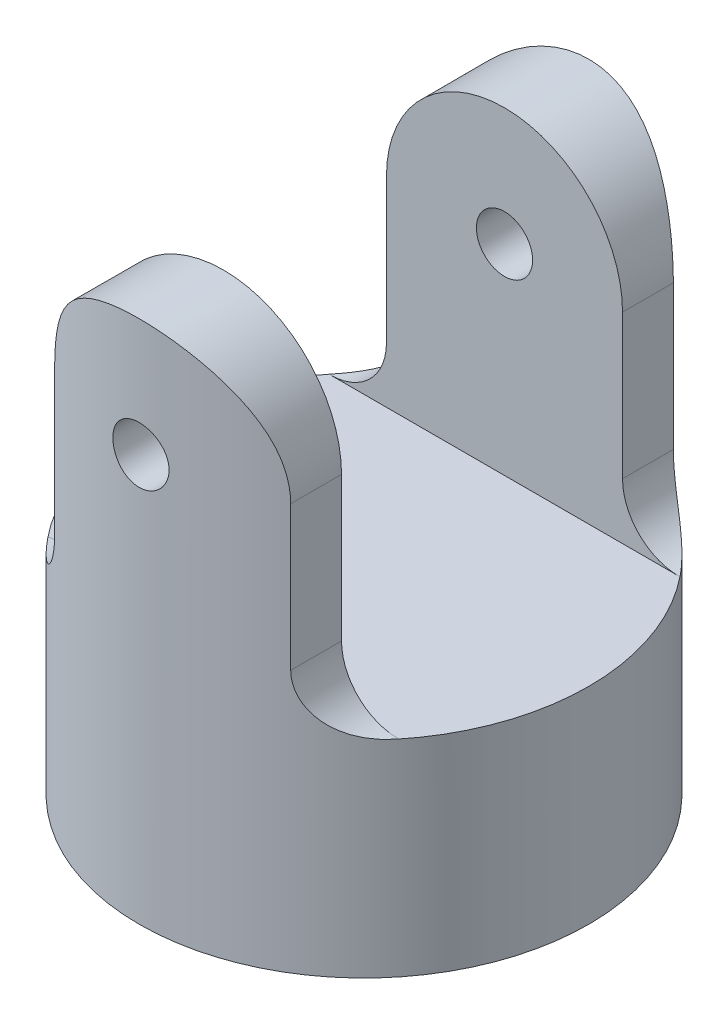
SolidWorks part; units mm, degrees
ref_plane "Front Plane" through (0, 0, 0) normal (0, 0, 1) x (1, 0, 0)
ref_plane "Top Plane" through (0, 0, 0) normal (0, 1, 0) x (1, 0, 0)
ref_plane "Right Plane" through (0, 0, 0) normal (1, 0, 0) x (0, 0, -1)
sketch "Sketch1" plane through (0, 0, 0) normal (0, 1, 0) x (1, 0, 0)
  circle A0 centre (0, 0) radius 6
  dimension "D1" = 12
extrude "Boss-Extrude1" add sketch "Sketch1" along normal blind 14
sketch "Sketch2" plane through (0, 0, 0) normal (1, 0, 0) x (0, 0, -1)
  line L0 (6, 14) -> (-6, 14) construction
  line L1 (-3.75, 14) -> (3.75, 14)
  line L2 (-3.75, 14) -> (-3.75, 5.5)
  line L3 (-3.75, 5.5) -> (3.75, 5.5)
  line L4 (3.75, 14) -> (3.75, 5.5)
  line L5 (-6, 0) -> (6, 0) construction
  point P8 (0, 5.5)
  dimension "D1" = 5.5
  dimension "D2" = 7.5
extrude "Cut-Extrude1" cut sketch "Sketch2" against normal through all both and the other way through all contours L2 L1 L4 L3
sketch "Sketch3" plane through (0, 0, 0) normal (0, 0, 1) x (1, 0, 0)
  line L0 (4.6837, 14) -> (-4.6837, 14) construction
  line L1 (-3.15, 10.85) -> (-3.15, 7)
  line L2 (-4.65, 5.5) -> (-4.6837, 5.5)
  line L3 (-4.6837, 14) -> (-4.6837, 5.5) construction
  line L4 (4.6837, 14) -> (-4.6837, 14)
  line L5 (-4.6837, 14) -> (-4.6837, 5.5)
  line L7 (0, -6.6) -> (0, 6.6) construction
  line L8 (4.6837, 14) -> (4.6837, 5.5)
  line L9 (4.65, 5.5) -> (4.6837, 5.5)
  line L10 (3.15, 10.85) -> (3.15, 7)
  arc A0 (3.15, 10.85) -> (-3.15, 10.85) centre (0, 10.85) ccw
  arc A1 (-3.15, 7) -> (-4.65, 5.5) centre (-4.65, 7) cw
  arc A2 (3.15, 7) -> (4.65, 5.5) centre (4.65, 7) ccw
  circle A3 centre (0, 10.85) radius 0.75
  dimension "D1" = 6.3
  dimension "D2" = 1.5
  dimension "D3" = 1.5
extrude "Cut-Extrude2" cut sketch "Sketch3" against normal through all both and the other way through all contours A1 L1 A0 L4 L5 L2 | L10 A2 L9 L8 L4 A0 | A3
